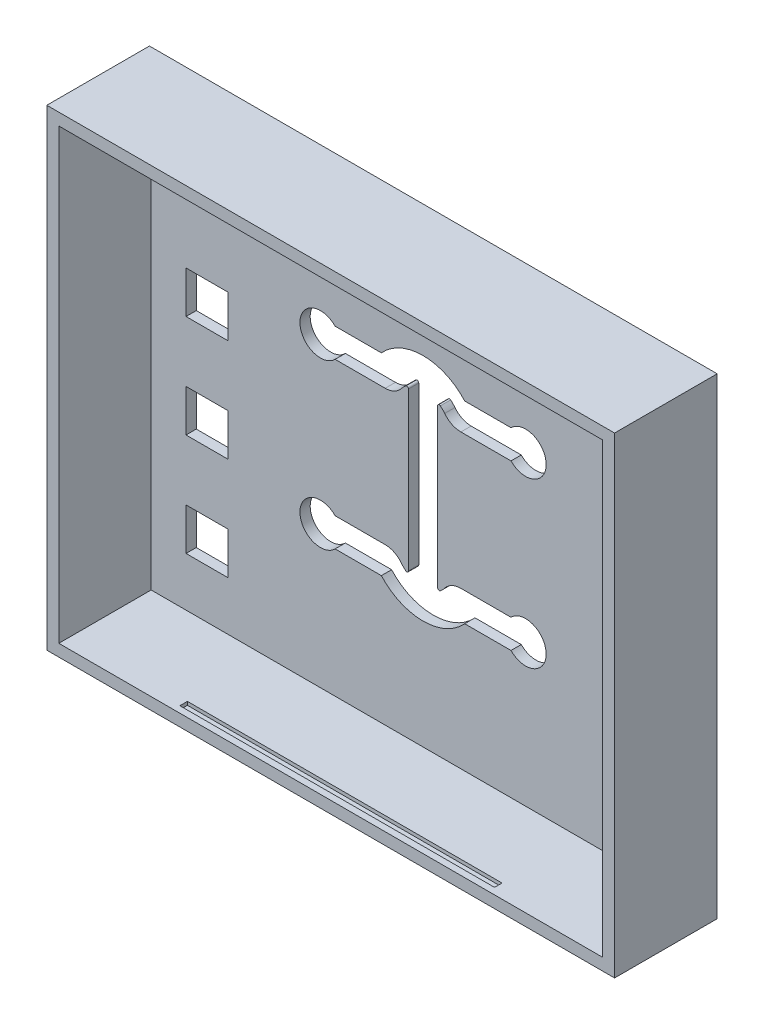
SolidWorks part; units mm, degrees
ref_plane "정면" through (0, 0, 0) normal (0, 0, 1) x (1, 0, 0)
ref_plane "윗면" through (0, 0, 0) normal (0, 1, 0) x (1, 0, 0)
ref_plane "우측면" through (0, 0, 0) normal (1, 0, 0) x (0, 0, -1)
sketch "스케치1" plane through (0, 0, 0) normal (0, 0, 1) x (1, 0, 0)
  line L1 (-83, -69) -> (83, -69)
  line L2 (-83, -69) -> (-83, 69)
  line L3 (-83, 69) -> (83, 69)
  line L4 (83, -69) -> (83, 69)
  line L5 (-83, -69) -> (83, 69) construction
  line L6 (-83, 69) -> (83, -69) construction
  point P0 (0, 0)
  dimension "D1" = 166
  dimension "D2" = 138
extrude "보스-돌출1" add sketch "스케치1" along normal blind 3
sketch "스케치2" plane through (0, 0, 3) normal (0, 0, 1) x (1, 0, 0)
  line L1 (-83, -69) -> (83, -69)
  line L2 (-83, -69) -> (-83, 69)
  line L3 (-83, 69) -> (83, 69)
  line L4 (83, -69) -> (83, 69)
  line L5 (-83, -69) -> (83, 69) construction
  line L6 (-83, 69) -> (83, -69) construction
  line L7 (-79.5, -65.5) -> (79.5, -65.5)
  line L8 (-79.5, -65.5) -> (-79.5, 65.5)
  line L9 (-79.5, 65.5) -> (79.5, 65.5)
  line L10 (79.5, -65.5) -> (79.5, 65.5)
  line L11 (-79.5, -65.5) -> (79.5, 65.5) construction
  line L12 (-79.5, 65.5) -> (79.5, -65.5) construction
  point P0 (0, 0)
  point P7 (0, 0)
  line M9 (83, -69) -> (83, 69)
  line M10 (83, 69) -> (-83, 69)
  line M11 (-83, 69) -> (-83, -69)
  line M12 (-83, -69) -> (83, -69)
  dimension "D1" = 159
  dimension "D2" = 131
extrude "보스-돌출2" add sketch "스케치2" along normal blind 27 contours L10 L7 L8 L9 M12 M9 M10 M11
sketch "스케치3" plane through (0, 65.5, 0) normal (0, -1, 0) x (1, 0, 0)
  line L0 (-79.5, 30) -> (79.5, 30) construction
  line L1 (-46, 28.1) -> (46, 28.1)
  line L2 (-46, 28.1) -> (-46, 25.9)
  line L3 (-46, 25.9) -> (46, 25.9)
  line L4 (46, 28.1) -> (46, 25.9)
  line L5 (-46, 28.1) -> (46, 25.9) construction
  line L6 (-46, 25.9) -> (46, 28.1) construction
  point P0 (0, 27)
  point P7 (0, 30)
  dimension "D1" = 2.2
  dimension "D2" = 92
  dimension "D3" = 0
  dimension "D4" = 3
extrude "컷-돌출1" cut sketch "스케치3" against normal blind 1
sketch "스케치4" plane through (0, -65.5, 0) normal (0, 1, 0) x (1, 0, 0)
  line L0 (-79.5, -30) -> (79.5, -30) construction
  line L1 (-46, -28.1) -> (46, -28.1)
  line L2 (-46, -28.1) -> (-46, -25.9)
  line L3 (-46, -25.9) -> (46, -25.9)
  line L4 (46, -28.1) -> (46, -25.9)
  line L5 (-46, -28.1) -> (46, -25.9) construction
  line L6 (-46, -25.9) -> (46, -28.1) construction
  point P0 (0, -27)
  point P7 (0, -30)
  dimension "D1" = 92
  dimension "D2" = 2.2
  dimension "D3" = 0
  dimension "D4" = 3
extrude "컷-돌출2" cut sketch "스케치4" against normal blind 1
sketch "스케치11" plane through (0, 0, 0) normal (0, 0, -1) x (-1, 0, 0)
  line L0 (63.15, 69) -> (63.15, -69) construction
  line L1 (-83, 69) -> (83, 69) construction
  line L2 (83, -69) -> (-83, -69) construction
  line L3 (83, 69) -> (83, -69) construction
  line L4 (57, 8.85) -> (57, 21.15)
  line L5 (57, 38.85) -> (69.3, 38.85)
  line L6 (57, 38.85) -> (57, 51.15)
  line L7 (57, 51.15) -> (69.3, 51.15)
  line L8 (69.3, 38.85) -> (69.3, 51.15)
  line L9 (57, 38.85) -> (69.3, 51.15) construction
  line L10 (57, 51.15) -> (69.3, 38.85) construction
  line L11 (57, 8.85) -> (69.3, 8.85)
  line L12 (69.3, 8.85) -> (69.3, 21.15)
  line L13 (57, 21.15) -> (69.3, 21.15)
  line L14 (57, -21.15) -> (57, -8.85)
  line L15 (57, -21.15) -> (69.3, -21.15)
  line L16 (69.3, -21.15) -> (69.3, -8.85)
  line L17 (57, -8.85) -> (69.3, -8.85)
  line L18 (57, -51.15) -> (57, -38.85)
  line L19 (57, -51.15) -> (69.3, -51.15)
  line L20 (69.3, -51.15) -> (69.3, -38.85)
  line L21 (57, -38.85) -> (69.3, -38.85)
  point P8 (63.15, 45)
  dimension "D1" = 19.85
  dimension "D2" = 12.3
  dimension "D3" = 12.3
  dimension "D4" = 24
  dimension "D5" = 4
extrude "컷-돌출8" cut sketch "스케치11" against normal blind 10
sketch "스케치15" plane through (0, 0, 0) normal (0, 0, -1) x (-1, 0, 0)
  line L0 (0, 0) -> (0, 69) construction
  line L1 (-83, 69) -> (83, 69) construction
  line L2 (0, 0) -> (83, 0) construction
  line L3 (83, 69) -> (83, -69) construction
  line L5 (30, -28.2) -> (-30, -28.2)
  line L6 (-4.25, -24) -> (4.25, -24)
  line L7 (-4.25, -24) -> (-4.25, 24)
  line L8 (-4.25, 24) -> (4.25, 24)
  line L9 (4.25, -24) -> (4.25, 24)
  line L10 (-4.25, -24) -> (4.25, 24) construction
  line L11 (-4.25, 24) -> (4.25, -24) construction
  line L12 (30, 19.8) -> (-30, 19.8)
  line L13 (30, 19.8) -> (30, 28.2)
  line L14 (30, 28.2) -> (-30, 28.2)
  line L15 (-30, 19.8) -> (-30, 28.2)
  line L16 (30, 19.8) -> (-30, 28.2) construction
  line L17 (30, 28.2) -> (-30, 19.8) construction
  line L18 (-30, -19.8) -> (-30, -28.2)
  line L19 (30, -19.8) -> (-30, -19.8)
  line L20 (30, -19.8) -> (30, -28.2)
  circle A1 centre (0, 17.2223) radius 8
  circle A2 centre (0, 17.2223) radius 16.4
  circle A7 centre (0, -17.2223) radius 8
  circle A8 centre (0, -17.2223) radius 16.4
  circle A14 centre (-30, 24) radius 6
  circle A15 centre (30, 24) radius 6
  circle A16 centre (30, -24) radius 6
  circle A17 centre (-30, -24) radius 6
  point P16 (0, 24)
  dimension "D5" = 8.4
  dimension "D4" = 8.5
extrude "컷-돌출12" cut sketch "스케치15" against normal blind 10
fillet "필렛1" radius 6 4 edges at (7.5733, -19.8, 1.5) (-7.5733, -19.8, 1.5) (-7.5733, 19.8, 1.5) (7.5733, 19.8, 1.5)
fillet "필렛2" radius 0.5 4 edges at (-4.25, -24, 1.5) (4.25, -24, 1.5) (-4.25, 24, 1.5) (4.25, 24, 1.5)
